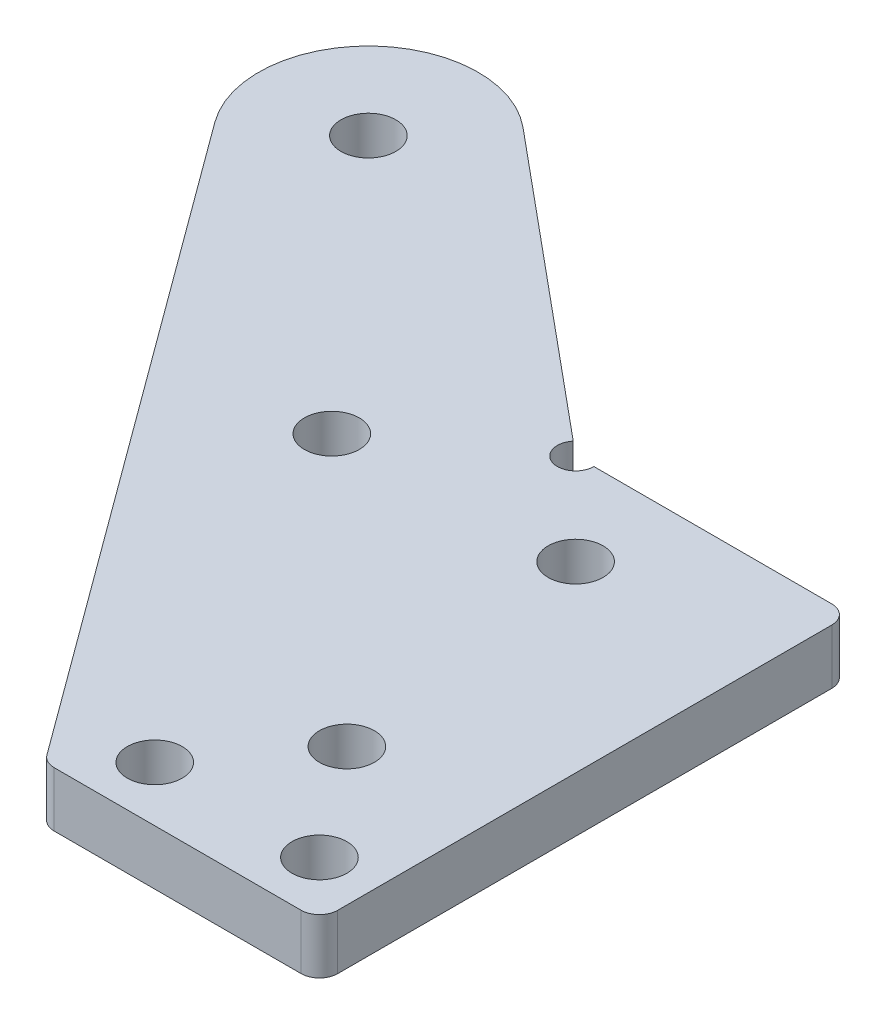
SolidWorks part; units mm, degrees
ref_plane "Front Plane" through (0, 0, 0) normal (0, 0, 1) x (1, 0, 0)
ref_plane "Top Plane" through (0, 0, 0) normal (0, 1, 0) x (1, 0, 0)
ref_plane "Right Plane" through (0, 0, 0) normal (1, 0, 0) x (0, 0, -1)
sketch "Sketch1" plane through (0, 0, 0) normal (0, 1, 0) x (1, 0, 0)
  line L0 (-16.991, 28.6152) -> (-0.7692, 15.139)
  line L1 (15, 14.5) -> (15, -14.5)
  line L2 (1, 14.5) -> (15, 14.5)
  line L3 (15, -14.5) -> (0, -14.5)
  line L4 (3, -11.5) -> (12, -11.5) construction
  line L5 (7.5, -14.5) -> (7.5, -5.5) construction
  line L6 (-25.6614, 20.4489) -> (0, -14.5)
  line L7 (0, -14.5) -> (0, 14.5) construction
  line L8 (-20.8251, 24) -> (0, 0) construction
  circle A0 centre (-20.8251, 24) radius 1.5
  arc A1 (-16.991, 28.6152) -> (-25.6614, 20.4489) centre (-20.8251, 24) ccw
  circle A2 centre (3, -11.5) radius 1.5
  circle A3 centre (12, -11.5) radius 1.5
  circle A4 centre (7.5, -5.5) radius 1.5
  circle A5 centre (5, 9.5) radius 1.5
  circle A6 centre (-7.7175, 8.894) radius 1.5
  arc A7 (-0.7692, 15.139) -> (1, 14.5) centre (0, 14.5) ccw
  point P13 (7.5, -11.5)
  point P21 (-25.6614, 20.4489)
  dimension "D1" = 3
  dimension "D2" = 6
  dimension "D5" = 3
  dimension "D10" = 3
  dimension "D15" = 2
  dimension "D3" = 9
  dimension "D4" = 9
  dimension "D6" = 3
  dimension "D7" = 29
  dimension "D8" = 10
  dimension "D9" = 5
  dimension "D11" = 20
  dimension "D12" = 15
  dimension "D13" = 43.3582
  dimension "D14" = 22.0892
  dimension "D16" = 14
extrude "Boss-Extrude1" add sketch "Sketch1" along normal blind 3
fillet "Fillet1" radius 1 3 edges at (15, 1.5, -14.5) (15, 1.5, 14.5) (0, 1.5, 14.5)
